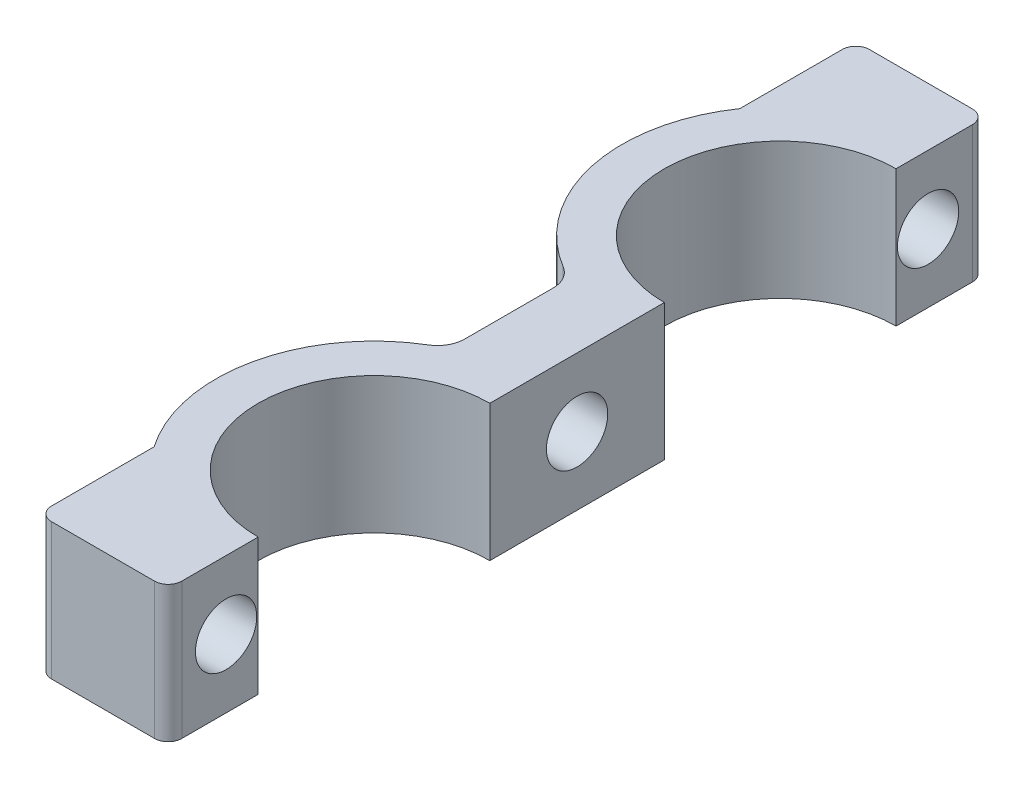
SolidWorks part; units mm, degrees
material "3.1355 (EN-AW 2024)"
ref_plane "Front" through (0, 0, 0) normal (0, 0, 1) x (1, 0, 0)
ref_plane "Top" through (0, 0, 0) normal (0, 1, 0) x (1, 0, 0)
ref_plane "Right" through (0, 0, 0) normal (1, 0, 0) x (0, 0, -1)
sketch "Эскиз1" plane through (0, 0, 0) normal (0, 1, 0) x (1, 0, 0)
  line L0 (0, 0) -> (0, 60) construction
  line L1 (0, 30) -> (-15.0292, 30) construction
  line L2 (0, 0) -> (0, 8)
  line L3 (0, 60) -> (0, 52)
  line L4 (0, 37.8) -> (0, 22.2)
  line L5 (-3, 0) -> (-3, 5.4558)
  line L6 (-3, 35.2558) -> (-3, 24.7442)
  line L7 (-3, 60) -> (-3, 54.5442)
  line L8 (-3, 60) -> (0, 60)
  line L9 (-3, 0) -> (0, 0)
  circle A0 centre (0, 15.1) radius 7.1 construction
  circle A1 centre (0, 44.9) radius 7.1 construction
  arc A2 (0, 8) -> (0, 22.2) centre (0, 15.1) cw
  arc A3 (0, 52) -> (0, 37.8) centre (0, 44.9) ccw
  arc A4 (-3, 5.4558) -> (-3, 24.7442) centre (0, 15.1) cw
  arc A5 (-3, 54.5442) -> (-3, 35.2558) centre (0, 44.9) ccw
  point P9 (0, 22.2)
  dimension "D2" = 15.1
  dimension "D3" = 14.2
  dimension "D1" = 60
  dimension "D4" = 3
extrude "Бобышка-Вытянуть1" add sketch "Эскиз1" along normal blind 10
sketch "Эскиз2" plane through (0, 10, 0) normal (0, 1, 0) x (1, 0, 0)
  line L0 (-3, 60) -> (-8.0498, 60)
  line L1 (-8.0498, 60) -> (-8.0498, 51)
  line L2 (-3, 60) -> (-3, 54.5442)
  line L3 (0, 30) -> (-3, 30) construction
  line L4 (0, 22.2) -> (0, 37.8) construction
  line L5 (-3, 35.2558) -> (-3, 24.7442) construction
  line L6 (-3, 0) -> (-3, 5.4558)
  line L7 (-8.0498, 0) -> (-8.0498, 9)
  line L8 (-3, 0) -> (-8.0498, 0)
  arc A0 (-3, 54.5442) -> (-3, 35.2558) centre (0, 44.9) ccw construction
  arc A1 (-3, 54.5442) -> (-8.0498, 51) centre (0, 44.9) ccw
  arc A2 (-3, 5.4558) -> (-8.0498, 9) centre (0, 15.1) cw
  dimension "D1" = 9
sketch "Эскиз3" plane through (0, 0, 0) normal (-1, 0, 0) x (0, 0, 1)
  line L0 (-60, 5) -> (-54.7288, 5) construction
  line L1 (-60, 10) -> (-60, 0) construction
  line L3 (-30, 10) -> (-30, 0) construction
  line L4 (-35.2558, 10) -> (-24.7442, 10) construction
  line L5 (-35.2558, 0) -> (-24.7442, 0) construction
  circle A0 centre (-55.75, 5) radius 2.25
  circle A1 centre (-4.25, 5) radius 2.25
  point P6 (-58, 5)
  point P7 (-53.5, 5)
  dimension "D1" = 4.5
  dimension "D2" = 2
extrude "Бобышка-Вытянуть2" add sketch "Эскиз2" against normal up to surface (10 mm away) up to face at (-3.8667, 0, -30)
sketch "Эскиз9" plane through (0, 0, 0) normal (0, -1, 0) x (1, 0, 0)
  line L1 (-8.0498, -9) -> (-8.0498, 0) construction
  line L2 (-5, -35.2558) -> (-5, -24.7442)
  line L3 (-5, -34.4329) -> (-5, -25.5671)
  line L4 (-8.0498, 0) -> (-8.0498, -9)
  line L6 (-9.5498, -60) -> (-8.0498, -60)
  line L7 (-3, -35.2558) -> (-3, -24.7442) construction
  line L8 (-3, -35.2558) -> (-3, -24.7442)
  line L9 (-8.0498, -9) -> (-8.0498, 0)
  line L10 (-9.5498, -8.5151) -> (-9.5498, 0)
  line L12 (-9.5498, 0) -> (-8.0498, 0)
  line L13 (-9.5498, -60) -> (-9.5498, -51)
  line L14 (-9.5498, -60) -> (-9.5498, -51.4849)
  line L15 (-8.0498, -60) -> (-8.0498, -51)
  line L16 (-9.5498, -9) -> (-9.5498, 0) construction
  arc A2 (-9.2454, -8.0941) -> (-3.4455, -26.1765) centre (0, -15.1) ccw
  arc A3 (-9.5498, -8.5151) -> (-5, -25.5671) centre (0, -15.1) ccw
  arc A4 (-8.0498, -9) -> (-3, -24.7442) centre (0, -15.1) ccw construction
  arc A5 (-3.4455, -33.8235) -> (-9.2454, -51.9059) centre (0, -44.9) ccw
  arc A6 (-5, -34.4329) -> (-9.5498, -51.4849) centre (0, -44.9) ccw
  arc A7 (-3, -35.2558) -> (-8.0498, -51) centre (0, -44.9) ccw construction
  arc A8 (-8.0498, -9) -> (-3, -24.7442) centre (0, -15.1) ccw
  arc A9 (-3, -35.2558) -> (-8.0498, -51) centre (0, -44.9) ccw
  dimension "D1" = 1.5
  dimension "D2" = 1.5
  dimension "D3" = 2
  dimension "D4" = 1.5
  dimension "D5" = 1.5
extrude "Бобышка-Вытянуть4" add sketch "Эскиз9" against normal through all
sketch "Эскиз4" plane through (-5, 0, 0) normal (-1, 0, 0) x (0, 0, 1)
  line L0 (-30, 10) -> (-30, 0) construction
  line L3 (-34.4329, 10) -> (-25.5671, 10) construction
  line L4 (-34.4329, 0) -> (-25.5671, 0) construction
  circle A0 centre (-30, 5) radius 2.25
  dimension "D1" = 4.5
extrude "Вырез-Вытянуть4" cut sketch "Эскиз3" along normal through all
extrude "Вырез-Вытянуть2" cut sketch "Эскиз4" against normal through all
fillet "Скругление2" radius 1 2 edges at (0, 5, 0) (0, 5, -60)
sketch "Эскиз5" plane through (0, 0, 0) normal (0, -1, 0) x (1, 0, 0)
  line L0 (0, -8) -> (0, -8.1)
  line L1 (0, -51.9) -> (0, -52)
  line L2 (0, -37.8) -> (0, -37.9)
  line L3 (0, -22.1) -> (0, -22.2)
  arc A0 (0, -8) -> (0, -22.2) centre (0, -15.1) ccw construction
  arc A1 (0, -37.8) -> (0, -52) centre (0, -44.9) ccw construction
  arc A2 (0, -8) -> (0, -22.2) centre (0, -15.1) ccw
  arc A3 (0, -37.8) -> (0, -52) centre (0, -44.9) ccw
  arc A4 (0, -8.1) -> (0, -22.1) centre (0, -15.1) ccw
  arc A5 (0, -37.9) -> (0, -51.9) centre (0, -44.9) ccw
  dimension "D1" = 0.1
extrude "Бобышка-Вытянуть3" add sketch "Эскиз5" against normal through all
sketch "Эскиз7" plane through (0, 10, 0) normal (0, 1, 0) x (1, 0, 0)
  line L0 (0, 51.9) -> (0, 59) construction
  line L1 (0, 22.1) -> (0, 37.9) construction
  line L2 (0, 1) -> (0, 8.1) construction
  line L3 (0, 51.9) -> (0, 53.4)
  line L4 (0, 22.1) -> (0, 23.6)
  line L5 (0, 6.6) -> (0, 8.1)
  line L6 (0, 36.4) -> (0, 37.9)
  arc A8 (0, 53.4) -> (0, 36.4) centre (0, 44.9) ccw
  arc A9 (0, 53.4) -> (0, 36.4) centre (0, 44.9) ccw
  arc A10 (0, 51.9) -> (0, 37.9) centre (0, 44.9) ccw construction
  arc A11 (0, 23.6) -> (0, 6.6) centre (0, 15.1) ccw
  arc A12 (0, 23.6) -> (0, 6.6) centre (0, 15.1) ccw
  arc A13 (0, 22.1) -> (0, 8.1) centre (0, 15.1) ccw construction
  arc A14 (0, 51.9) -> (0, 37.9) centre (0, 44.9) ccw
  arc A15 (0, 22.1) -> (0, 8.1) centre (0, 15.1) ccw
  dimension "D1" = 1.5
  dimension "D2" = 1.5
extrude "Вырез-Вытянуть3" cut sketch "Эскиз7" against normal through all
fillet "Скругление3" radius 1 2 edges at (-9.5498, 5, 0) (-9.5498, 5, -60)
fillet "Скругление4" radius 2 2 edges at (-5, 5, -34.4329) (-5, 5, -25.5671)
equation "\"D2@Эскиз1\"=8+\"D3@Эскиз1\"/2"
